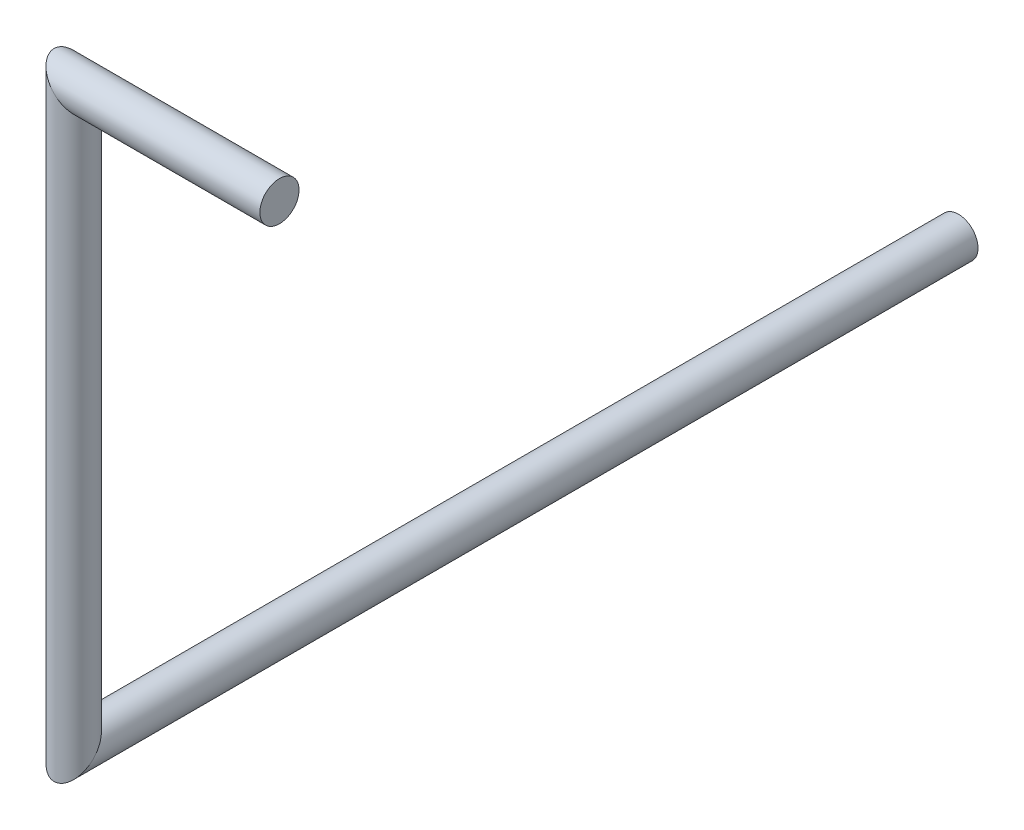
SolidWorks part; units mm, degrees
ref_plane "Alzado" through (0, 0, 0) normal (0, 0, 1) x (1, 0, 0)
ref_plane "Planta" through (0, 0, 0) normal (0, 1, 0) x (1, 0, 0)
ref_plane "Vista lateral" through (0, 0, 0) normal (1, 0, 0) x (0, 0, -1)
sketch "Croquis1" plane through (0, 0, 0) normal (0, 0, 1) x (1, 0, 0)
  circle A0 centre (0, 0) radius 9.525
  dimension "D1" = 19.05
extrude "Saliente-Extruir1" add sketch "Croquis1" along normal blind 10
sketch3d "Croquis3D1"
  line L0 (0, 0, 10) -> (0, 0, 430)
  line L1 (0, 0, 10) -> (0, 0, 0) construction
  line L2 (0, 0, 430) -> (0, 280, 430)
  line L3 (0, 280, 430) -> (100, 280, 430)
  dimension "D1" = 420
  dimension "D2" = 280
  dimension "D3" = 100
sketch "Croquis2" plane through (0, 0, 10) normal (0, 0, 1) x (1, 0, 0)
  circle A0 centre (0, 0) radius 9.525
sweep "Barrer1" add profiles "Croquis2" path "Croquis3D1"
